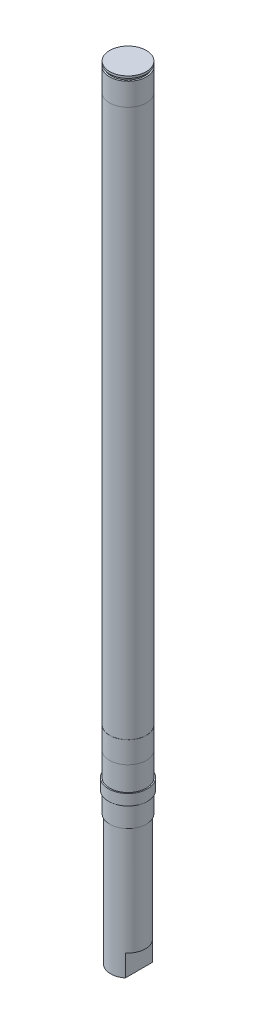
SolidWorks part; units mm, degrees
material "Alliage 6061"
ref_plane "Face" through (0, 0, 0) normal (0, 0, 1) x (1, 0, 0)
ref_plane "Dessus" through (0, 0, 0) normal (0, 1, 0) x (1, 0, 0)
ref_plane "Droite" through (0, 0, 0) normal (1, 0, 0) x (0, 0, -1)
sketch "Esquisse1" plane through (0, 0, 0) normal (0, 0, 1) x (1, 0, 0)
  line L0 (0, 0) -> (0, 360.5) construction
  line L1 (0, 0) -> (8, 0)
  line L2 (8.45, 85.5) -> (8.5, 85.5)
  line L3 (8.5, 95.5) -> (8.45, 95.5)
  line L4 (8.45, 95.5) -> (8.45, 348)
  line L5 (8.45, 60) -> (8.45, 69.4)
  line L6 (8.45, 359.5) -> (7.75, 359.5)
  line L7 (8.45, 360.5) -> (0, 360.5)
  line L8 (0, 0) -> (0, 360.5)
  line L9 (8.5, 85.5) -> (8.5, 95.5)
  line L10 (7.75, 359.5) -> (7.75, 358.4)
  line L11 (8.45, 60) -> (8, 60)
  line L12 (8.45, 359.5) -> (8.45, 360.5)
  line L13 (8.45, 348) -> (8.5, 348)
  line L14 (8.5, 348) -> (8.5, 358.4)
  line L15 (8.5, 358.4) -> (7.75, 358.4)
  line L16 (8, 60) -> (8, 0)
  line L17 (8.45, 74.4) -> (8.45, 85.5)
  line L18 (8.45, 74.4) -> (9, 74.4)
  line L19 (8.45, 69.4) -> (9, 69.4)
  line L20 (9, 74.4) -> (9, 69.4)
  dimension "D1" = 1.1
  dimension "D2" = 5
  dimension "D3" = 252.5
  dimension "D4" = 360.5
  dimension "D5" = 10
  dimension "D6" = 9
  dimension "D7" = 8.45
  dimension "D8" = 1
  dimension "D9" = 7.75
  dimension "D10" = 10.4
  dimension "D11" = 8.5
  dimension "D12" = 11.1
  dimension "D13" = 8
  dimension "D14" = 8.5
  dimension "D16" = 9.4
  dimension "D17" = 60
revolve "Révolution1" add sketch "Esquisse1" angle 360 about L0
sketch "Esquisse2" plane through (0, 0, 0) normal (0, -1, 0) x (1, 0, 0)
  line L1 (5, -12.3054) -> (-5, -12.3054)
  line L2 (5, -12.3054) -> (5, 12.3054)
  line L3 (5, 12.3054) -> (-5, 12.3054)
  line L4 (-5, -12.3054) -> (-5, 12.3054)
  line L5 (5, -12.3054) -> (-5, 12.3054) construction
  line L6 (5, 12.3054) -> (-5, -12.3054) construction
  point P0 (0, 0)
  dimension "D1" = 10
extrude "Extrusion1" cut sketch "Esquisse2" against normal blind 10 flip side to cut
